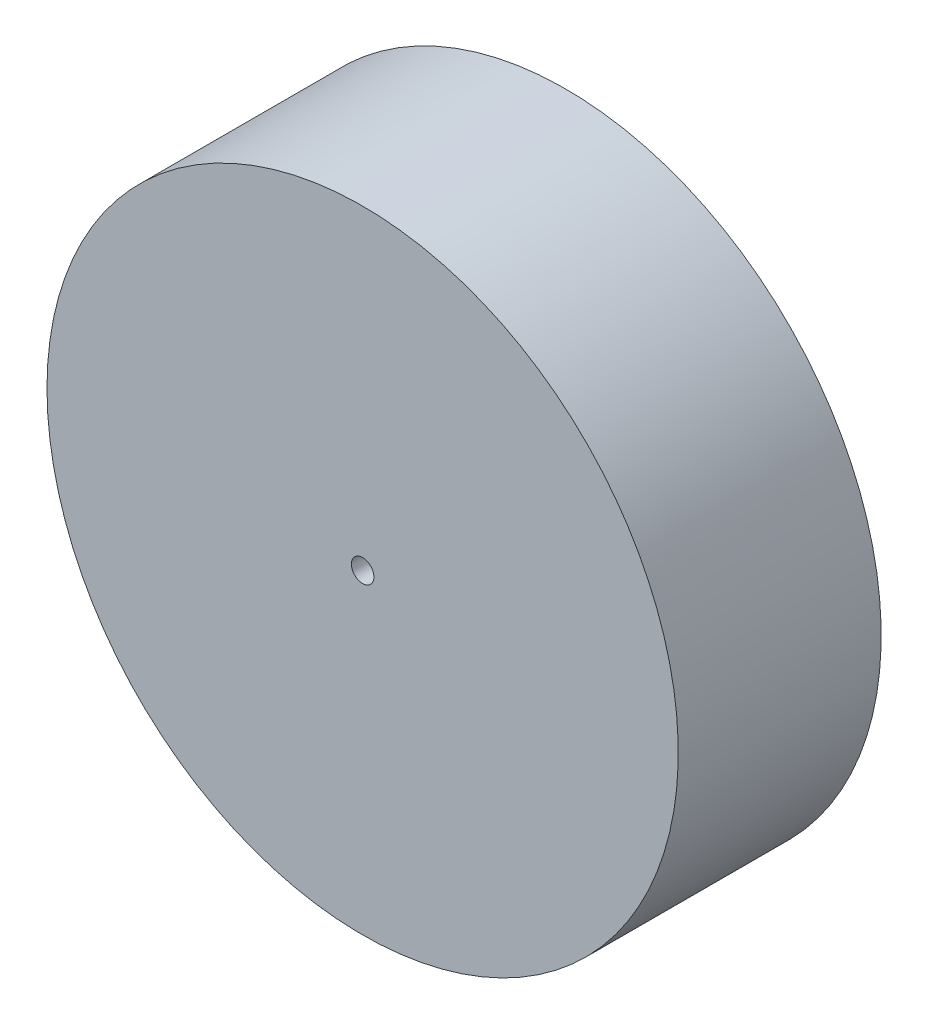
SolidWorks part; units mm, degrees
ref_plane "Front Plane" through (0, 0, 0) normal (0, 0, 1) x (1, 0, 0)
ref_plane "Top Plane" through (0, 0, 0) normal (0, 1, 0) x (1, 0, 0)
ref_plane "Right Plane" through (0, 0, 0) normal (1, 0, 0) x (0, 0, -1)
sketch "Sketch1" plane through (0, 0, 0) normal (0, 0, 1) x (1, 0, 0)
  circle A0 centre (0, 0) radius 70
  dimension "D1" = 140
extrude "Boss-Extrude1" add sketch "Sketch1" along normal blind 45
sketch "Sketch2" plane through (0, 0, 45) normal (0, 0, 1) x (1, 0, 0)
  circle A0 centre (0, 0) radius 2.5
  dimension "D1" = 5
extrude "Cut-Extrude1" cut sketch "Sketch2" against normal blind 20 and the other way through all
